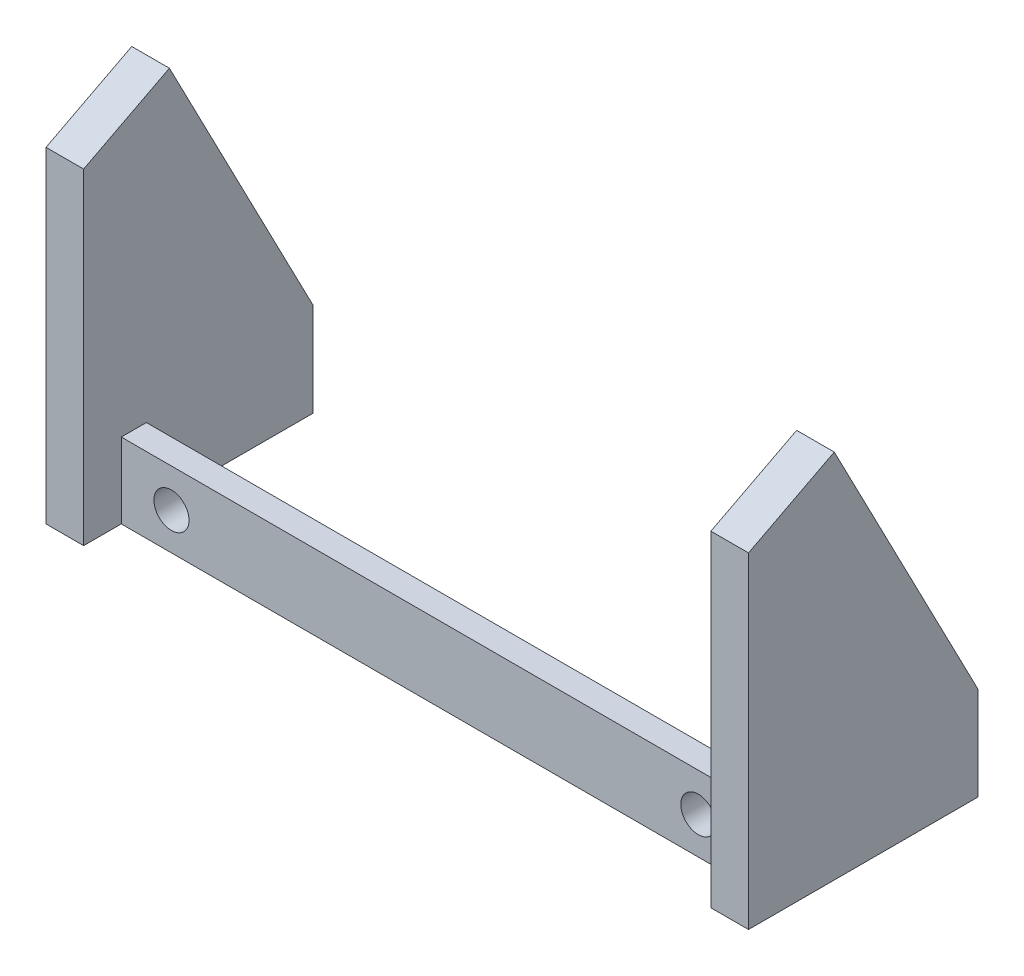
SolidWorks part; units mm, degrees
ref_plane "前视基准面" through (0, 0, 0) normal (0, 0, 1) x (1, 0, 0)
ref_plane "上视基准面" through (0, 0, 0) normal (0, 1, 0) x (1, 0, 0)
ref_plane "右视基准面" through (0, 0, 0) normal (1, 0, 0) x (0, 0, -1)
other "Configuration Table"
sketch "草图2" plane through (0, 0, 0) normal (1, 0, 0) x (0, 0, -1)
  line L1 (-47.1061, 81.5205) -> (-35.6484, 59.4224)
  line L5 (-35.6484, 51.9762) -> (-53.9419, 51.9762)
  line L6 (-53.9419, 51.9762) -> (-53.9419, 77.9762)
  line L7 (-47.1061, 81.5205) -> (-53.9419, 77.9762)
  line L8 (-35.6484, 59.4224) -> (-35.6484, 51.9762)
  dimension "D1" = 7.7
  dimension "D2" = 117.406
  dimension "D4" = 26
extrude "凸台-拉伸1" add sketch "草图2" along normal blind 3
ref_plane "基准面1" through (53, 0, 0) normal (1, 0, 0) x (0, 0, -1)
sketch "草图3" plane through (53, 0, 0) normal (1, 0, 0) x (0, 0, -1)
  line L5 (-47.1061, 81.5205) -> (-53.9419, 77.9762)
  line L6 (-53.9419, 77.9762) -> (-53.9419, 51.9762)
  line L7 (-53.9419, 51.9762) -> (-35.6484, 51.9762)
  line L8 (-35.6484, 51.9762) -> (-35.6484, 59.4224)
  line L9 (-35.6484, 59.4224) -> (-47.1061, 81.5205)
  line L10 (-47.1061, 81.5205) -> (-53.9419, 77.9762)
  line L11 (-53.9419, 77.9762) -> (-53.9419, 51.9762)
  line L12 (-53.9419, 51.9762) -> (-35.6484, 51.9762)
  line L14 (-35.6484, 59.4224) -> (-47.1061, 81.5205)
  line L15 (-35.6484, 51.9762) -> (-35.6484, 59.4224)
  dimension "D1" = 0
extrude "凸台-拉伸2" add sketch "草图3" along normal blind 3 separate body
sketch "草图5" plane through (3, 0, 0) normal (1, 0, 0) x (0, 0, -1)
  line L0 (-53.9419, 51.9762) -> (-35.6484, 51.9762) construction
  line L1 (-50.9419, 51.9762) -> (-48.9419, 51.9762)
  line L2 (-50.9419, 51.9762) -> (-50.9419, 57.9762)
  line L3 (-50.9419, 57.9762) -> (-48.9419, 57.9762)
  line L4 (-48.9419, 51.9762) -> (-48.9419, 57.9762)
  dimension "D1" = 2
  dimension "D2" = 6
extrude "凸台-拉伸3" add sketch "草图5" along normal up to next
sketch "草图8" plane through (0, 0, 48.9419) normal (0, 0, -1) x (-1, 0, 0)
  circle A0 centre (-49, 54.9239) radius 1.4
  circle A1 centre (-7, 54.9239) radius 1.4
  dimension "D1" = 2.8
extrude "切除-拉伸1" cut sketch "草图8" against normal up to next
